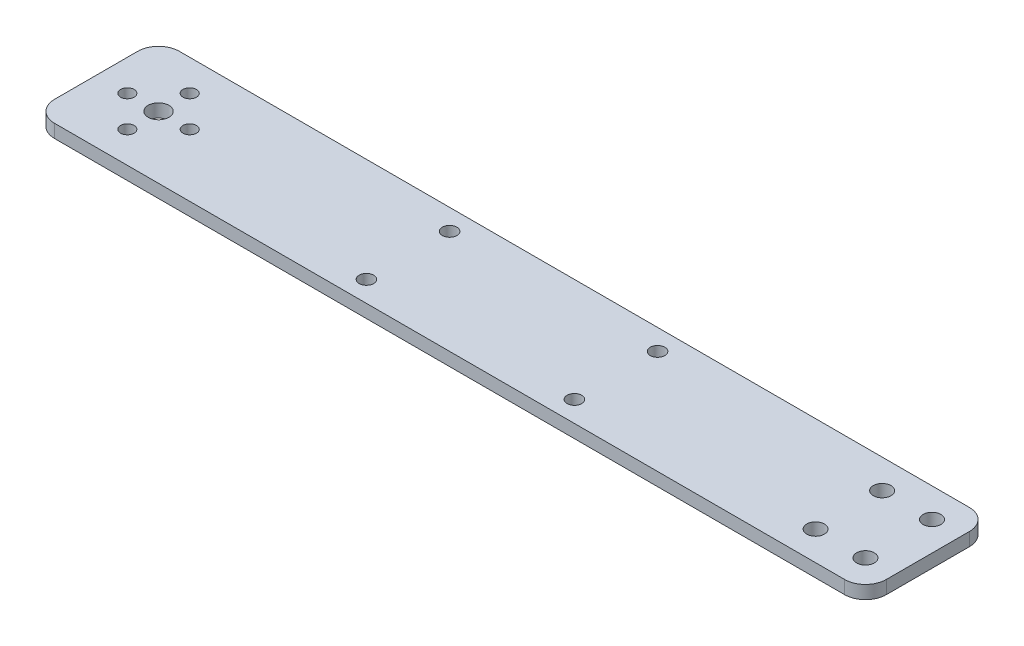
SolidWorks part; units mm, degrees
ref_plane "Front Plane" through (0, 0, 0) normal (0, 0, 1) x (1, 0, 0)
ref_plane "Top Plane" through (0, 0, 0) normal (0, 1, 0) x (1, 0, 0)
ref_plane "Right Plane" through (0, 0, 0) normal (1, 0, 0) x (0, 0, -1)
sketch "Sketch1" plane through (0, 0, 0) normal (0, 1, 0) x (1, 0, 0)
  line L1 (-15, 15) -> (185, 15)
  line L2 (-15, 15) -> (-15, -15)
  line L3 (-15, -15) -> (185, -15)
  line L4 (185, 15) -> (185, -15)
  point P4 (-15, 0)
  dimension "D1" = 200
  dimension "D2" = 30
  dimension "D3" = 15
extrude "Boss-Extrude1" add sketch "Sketch1" along normal blind 3.175
fillet "Fillet1" radius 5 4 edges at (185, 1.5875, 15) (185, 1.5875, -15) (-15, 1.5875, -15) (-15, 1.5875, 15)
sketch "Sketch2" plane through (0, 3.175, 0) normal (0, 1, 0) x (1, 0, 0)
  circle A6 centre (0, 0) radius 2.5
  dimension "D6" = 5
extrude "Cut-Extrude1" cut sketch "Sketch2" against normal through all
sketch "Sketch3" plane through (0, 3.175, 0) normal (0, 1, 0) x (1, 0, 0)
  line L0 (-15, 10) -> (-15, -10) construction
  circle A4 centre (7.5, 0) radius 1.625
  circle A5 centre (0, 0) radius 2.5 construction
  circle A6 centre (0, -7.5) radius 1.625
  circle A7 centre (-7.5, 0) radius 1.625
  circle A8 centre (0, 7.5) radius 1.625
  point P7 (-15, 0)
  dimension "D1" = 7.5
  dimension "D2" = 3.25
  dimension "D3" = 15
extrude "Cut-Extrude3" cut sketch "Sketch3" against normal through all
sketch "Sketch4" plane through (0, 3.175, 0) normal (0, 1, 0) x (1, 0, 0)
  line L0 (-15, 0) -> (185, 0) construction
  line L1 (-15, 10) -> (-15, -10) construction
  line L2 (185, -10) -> (185, 10) construction
  line L3 (85, 15) -> (85, -15) construction
  line L4 (180, 15) -> (-10, 15) construction
  line L5 (-10, -15) -> (180, -15) construction
  line L6 (110, -10) -> (150, -10) construction
  circle A0 centre (60, -10) radius 1.75
  circle A1 centre (110, -10) radius 1.75
  circle A2 centre (110, 10) radius 1.75
  circle A3 centre (60, 10) radius 1.75
  dimension "D3" = 3.5
  dimension "D1" = 25
  dimension "D2" = 5
  dimension "D4" = 40
extrude "Cut-Extrude4" cut sketch "Sketch4" against normal blind 10
sketch "Sketch5" plane through (0, 3.175, 0) normal (0, 1, 0) x (1, 0, 0)
  line L0 (172, 15) -> (172, -15) construction
  line L1 (180, 15) -> (-10, 15) construction
  line L2 (-10, -15) -> (180, -15) construction
  line L3 (185, 0) -> (-15, 0) construction
  line L4 (185, -10) -> (185, 10) construction
  line L5 (-15, 10) -> (-15, -10) construction
  circle A0 centre (166, 8) radius 2.125
  circle A1 centre (178, 8) radius 2.125
  circle A2 centre (178, -8) radius 2.125
  circle A3 centre (166, -8) radius 2.125
  dimension "D2" = 4.25
  dimension "D1" = 6
  dimension "D3" = 8
  dimension "D4" = 13
extrude "Cut-Extrude5" cut sketch "Sketch5" against normal through all
